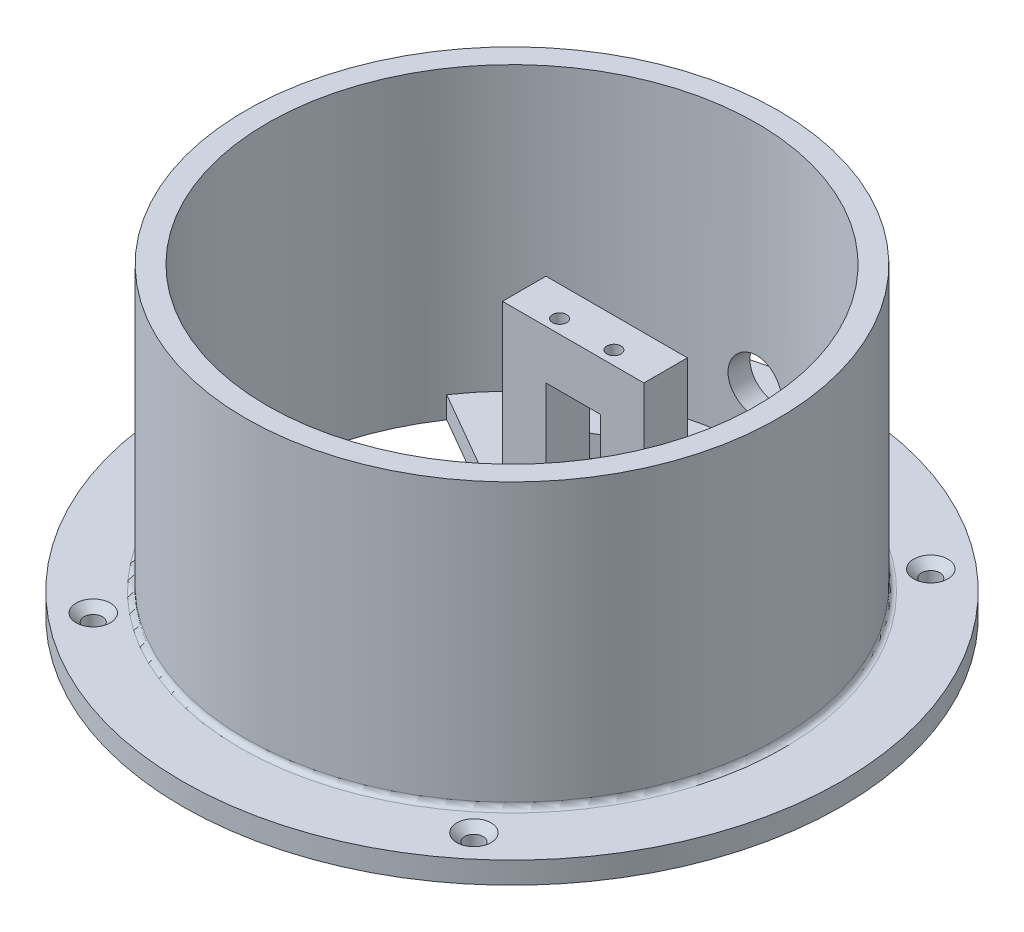
SolidWorks part; units mm, degrees
ref_plane "Front Plane" through (0, 0, 0) normal (0, 0, 1) x (1, 0, 0)
ref_plane "Top Plane" through (0, 0, 0) normal (0, 1, 0) x (1, 0, 0)
ref_plane "Right Plane" through (0, 0, 0) normal (1, 0, 0) x (0, 0, -1)
sketch "Sketch1" plane through (0, 0, 0) normal (0, 1, 0) x (1, 0, 0)
  circle A0 centre (0, 0) radius 60.625
  circle A1 centre (0, 0) radius 45
  dimension "D1" = 121.25
  dimension "D2" = 90
extrude "Boss-Extrude1" add sketch "Sketch1" along normal blind 4
sketch "Sketch2" plane through (0, 4, 0) normal (0, 1, 0) x (1, 0, 0)
  circle A0 centre (0, 0) radius 45 construction
  circle A1 centre (0, 0) radius 45
  circle A2 centre (0, 0) radius 49
  dimension "D1" = 4
extrude "Boss-Extrude2" add sketch "Sketch2" along normal blind 52
sketch "Sketch3" plane through (0, 0, 0) normal (1, 0, 0) x (0, 0, -1)
  line L0 (-46.75, 30) -> (-31.75, 30)
  line L1 (-31.75, 30) -> (-31.75, 38)
  line L2 (-31.75, 38) -> (-46.75, 38)
  line L3 (-46.75, 38) -> (-46.75, 30)
  line L4 (-45, 56) -> (-45, 0)
  line L5 (-31.75, 38) -> (-45, 24.75)
  line L6 (-45, 0) -> (45, 0) construction
  line L7 (11.25, 38) -> (19.25, 38)
  line L8 (11.25, 38) -> (11.25, 0)
  line L9 (11.25, 0) -> (19.25, 0)
  line L10 (19.25, 38) -> (19.25, 0)
  line L11 (11.25, 38) -> (19.25, 0) construction
  line L12 (11.25, 0) -> (19.25, 38) construction
  line L13 (49, 56) -> (-49, 56) construction
  line L14 (45, 56) -> (-45, 56) construction
  point P8 (15.25, 19)
  dimension "D1" = 8
  dimension "D2" = 18
  dimension "D3" = 11.25
  dimension "D4" = 43
  dimension "D5" = 15
  dimension "D6" = 45
  dimension "D7" = 8
  dimension "D8" = 18
extrude "Boss-Extrude3" add sketch "Sketch3" along normal mid plane 26 contours L10 L7 L8 L9 | L5 L2 L4 L0 | L5 L0 L4 | L1 L5 L0
sketch "Sketch6" plane through (0, 0, -11.25) normal (0, 0, 1) x (1, 0, 0)
  line L0 (13, 38) -> (-13, 38) construction
  line L5 (-5, 29) -> (5, 29)
  line L6 (-5, 29) -> (-5, 5)
  line L7 (-5, 5) -> (5, 5)
  line L8 (5, 29) -> (5, 5)
  line L9 (-5, 29) -> (5, 5) construction
  line L10 (-5, 5) -> (5, 29) construction
  point P0 (0, 17)
  point P8 (0, 5)
  dimension "D1" = 10
  dimension "D2" = 9
  dimension "D3" = 5
extrude "Cut-Extrude1" cut sketch "Sketch6" against normal blind 26
sketch "Sketch7" plane through (0, 0, -11.25) normal (0, 0, 1) x (1, 0, 0)
  line L0 (0, 56) -> (0, 0) construction
  circle A0 centre (0, 14) radius 5
  dimension "D1" = 10
  dimension "D2" = 14
extrude "Cut-Extrude2" cut sketch "Sketch7" against normal blind 58
sketch "Sketch8" plane through (0, 38, 0) normal (0, 1, 0) x (1, 0, 0)
  line L0 (-5, 13.75) -> (5, 13.75) construction
  line L1 (-5, -34.25) -> (5, -34.25) construction
  line L2 (13, -31.75) -> (-13, -31.75) construction
  circle A0 centre (-5, 13.75) radius 1.3
  circle A1 centre (5, 13.75) radius 1.3
  circle A2 centre (-5, -34.25) radius 1.3
  circle A3 centre (5, -34.25) radius 1.3
  dimension "D1" = 2.6
  dimension "D2" = 5
  dimension "D3" = 10
  dimension "D4" = 10
  dimension "D5" = 2.5
  dimension "D6" = 48
extrude "Cut-Extrude3" cut sketch "Sketch8" against normal blind 7.2
sketch "Sketch9" plane through (0, 0, 0) normal (0, -1, 0) x (1, 0, 0)
  line L0 (13, -11.25) -> (-13, -11.25) construction
  line L1 (13, -11.25) -> (-13, -11.25)
  line L2 (-13, -11.25) -> (-37.2484, -25.2498)
  line L3 (0, 0) -> (0, -24.2081) construction
  line L4 (13, -11.25) -> (37.2484, -25.2498)
  line L6 (-19.5167, -24.25) -> (-24.9065, -27.3618)
  line L7 (19.5167, -24.25) -> (24.9065, -27.3618)
  line L8 (-19.5167, -24.25) -> (19.5167, -24.25)
  line L9 (-10.8564, -19.25) -> (-24.9065, -27.3618) construction
  line L10 (10.8564, -19.25) -> (-10.8564, -19.25) construction
  line L11 (10.8564, -19.25) -> (24.9065, -27.3618) construction
  line L12 (13, -19.25) -> (-13, -19.25) construction
  circle A0 centre (0, 0) radius 45 construction
  arc A1 (-37.2484, -25.2498) -> (37.2484, -25.2498) centre (0, 0) ccw
  arc A2 (-24.9065, -27.3618) -> (24.9065, -27.3618) centre (0, 0) ccw
  dimension "D1" = 60
  dimension "D3" = 5
  dimension "D2" = 8
extrude "Boss-Extrude4" add sketch "Sketch9" against normal blind 4
sketch "Sketch10" plane through (0, 4, 0) normal (0, 1, 0) x (1, 0, 0)
  line L1 (-35, -42) -> (35, -42) construction
  line L2 (-35, -42) -> (-35, 42) construction
  line L3 (-35, 42) -> (35, 42) construction
  line L4 (35, -42) -> (35, 42) construction
  line L5 (-35, -42) -> (35, 42) construction
  line L6 (-35, 42) -> (35, -42) construction
  point P0 (0, 0)
  dimension "D1" = 84
  dimension "D2" = 70
hole_wizard "CSK for M3 Countersunk Flat Head Screw1" positions "Sketch11" profile "Sketch12" countersink size "M3" standard "DIN"
sketch "Sketch11" plane through (0, 4, 0) normal (0, 1, 0) x (1, 0, 0)
  point P0 (-35, 42)
  point P3 (35, 42)
  point P6 (35, -42)
  point P9 (-35, -42)
sketch "Sketch12" plane through (-35, 4, -42) normal (1, 0, 0) x (0, 0, 1)
  line L0 (0, 0) -> (0, 5.0215)
  line L1 (0, 5.0215) -> (1.7, 4)
  line L2 (1.7, 4) -> (1.7, 1.45)
  line L3 (1.7, 1.45) -> (3.15, 0)
  line L5 (3.15, 0) -> (0, 0)
  line L6 (-1.7, 1.45) -> (-3.15, 0) construction
  line L10 (0, 5.0215) -> (-1.7, 4) construction
  line L11 (0, -6.35) -> (0, 107.95) construction
  dimension "Hole Dia." = 3.4
  dimension "Hole Depth" = 4
  dimension "Near C'Sink Dia." = 6.3
  dimension "Near C'Sink Angle" = 90
  dimension "Drill Angle" = 118
fillet "Fillet1" radius 1 1 edges at (0, 4, 49)
